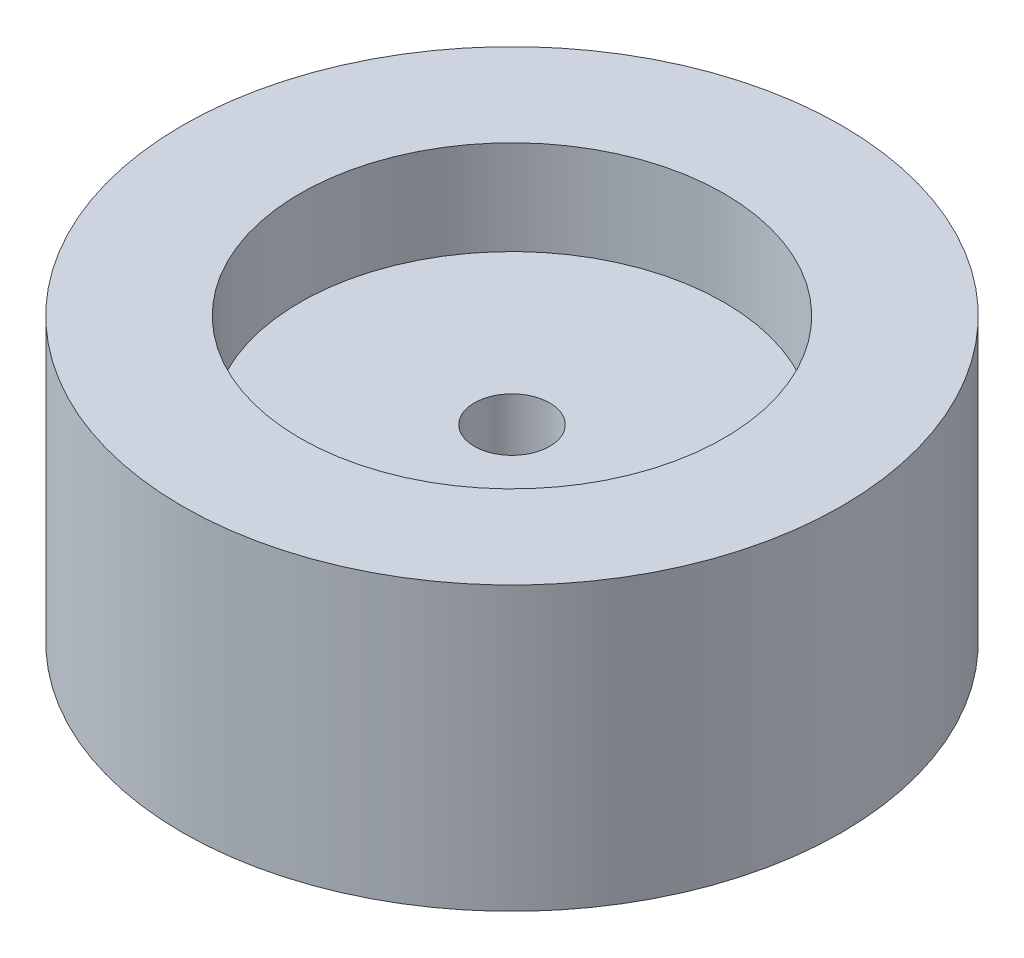
SolidWorks part; units mm, degrees
ref_plane "Front Plane" through (0, 0, 0) normal (0, 0, 1) x (1, 0, 0)
ref_plane "Top Plane" through (0, 0, 0) normal (0, 1, 0) x (1, 0, 0)
ref_plane "Right Plane" through (0, 0, 0) normal (1, 0, 0) x (0, 0, -1)
sketch "Sketch1" plane through (0, 0, 0) normal (0, 1, 0) x (1, 0, 0)
  circle A0 centre (0, 0) radius 35
  dimension "D1" = 70
extrude "Boss-Extrude1" add sketch "Sketch1" along normal blind 30
sketch "Sketch2" plane through (0, 30, 0) normal (0, 1, 0) x (1, 0, 0)
  circle A0 centre (0, 0) radius 22.5
  dimension "D1" = 45
extrude "Cut-Extrude1" cut sketch "Sketch2" against normal blind 10
sketch "Sketch3" plane through (0, 0, 0) normal (0, -1, 0) x (1, 0, 0)
  circle A0 centre (0, 0) radius 22.5
  dimension "D1" = 45
extrude "Cut-Extrude2" cut sketch "Sketch3" against normal blind 10
sketch "Sketch4" plane through (0, 10, 0) normal (0, -1, 0) x (1, 0, 0)
  circle A0 centre (0, 0) radius 4
  dimension "D1" = 8
extrude "Cut-Extrude3" cut sketch "Sketch4" against normal blind 10
